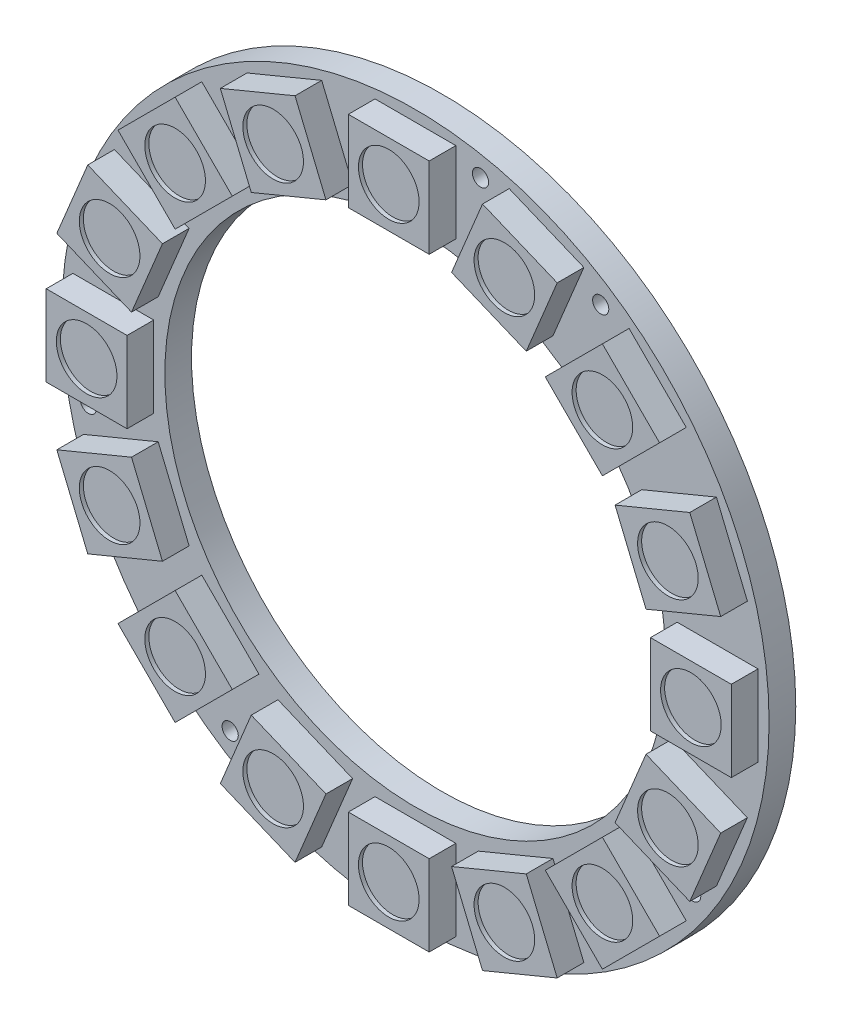
SolidWorks part; units mm, degrees
ref_plane "Front Plane" through (0, 0, 0) normal (0, 0, 1) x (1, 0, 0)
ref_plane "Top Plane" through (0, 0, 0) normal (0, 1, 0) x (1, 0, 0)
ref_plane "Right Plane" through (0, 0, 0) normal (1, 0, 0) x (0, 0, -1)
sketch "Sketch1" plane through (0, 0, 0) normal (0, 0, 1) x (1, 0, 0)
  circle A0 centre (0, 0) radius 15.748
  circle A1 centre (0, 0) radius 22.225
  dimension "D1" = 31.496
  dimension "D2" = 44.45
extrude "Boss-Extrude1" add sketch "Sketch1" along normal blind 1.6764
sketch "Sketch2" plane through (0, 0, 1.6764) normal (0, 0, 1) x (1, 0, 0)
  line L0 (0, 0) -> (0, 15.748) construction
  line L1 (0, 15.748) -> (0, 18.9865) construction
  line L2 (-2.54, 21.5265) -> (2.54, 21.5265)
  line L3 (-2.54, 21.5265) -> (-2.54, 16.4465)
  line L4 (-2.54, 16.4465) -> (2.54, 16.4465)
  line L5 (2.54, 21.5265) -> (2.54, 16.4465)
  line L6 (-2.54, 21.5265) -> (2.54, 16.4465) construction
  line L7 (-2.54, 16.4465) -> (2.54, 21.5265) construction
  line L8 (0, 18.9865) -> (0, 22.225) construction
  circle A0 centre (0, 0) radius 15.748 construction
  circle A1 centre (0, 0) radius 22.225 construction
  point P6 (0, 18.9865)
  dimension "D1" = 5.08
  dimension "D2" = 5.08
extrude "Boss-Extrude2" add sketch "Sketch2" along normal blind 1.6764
sketch "Sketch3" plane through (0, 0, 3.3528) normal (0, 0, 1) x (1, 0, 0)
  line L0 (0, 16.4465) -> (0, 21.5265) construction
  line L1 (-2.54, 16.4465) -> (2.54, 16.4465) construction
  line L2 (2.54, 21.5265) -> (-2.54, 21.5265) construction
  circle A0 centre (0, 18.9865) radius 1.905
  point P8 (0.4998, 19.7134)
  dimension "D1" = 3.81
extrude "Cut-Extrude1" cut sketch "Sketch3" against normal blind 0.254
pattern_circular "CirPattern1" count 16 over 360 about axis through (0, 0, 0) along (0, 0, 1) of "Cut-Extrude1", "Boss-Extrude2"
sketch "Sketch4" plane through (0, 0, 1.6764) normal (0, 0, 1) x (1, 0, 0)
  line L0 (4.0881, 20.5524) -> (4.3359, 21.798) construction
  line L1 (4.0881, 20.5524) -> (0, 0) construction
  line L2 (4.1872, 21.0506) -> (4.5674, 20.975) construction
  line L3 (2.54, 16.4465) -> (3.2436, 16.3066) construction
  line L4 (3.2436, 16.3066) -> (3.9471, 16.1666) construction
  circle A0 centre (4.0881, 20.5524) radius 0.508
  circle A1 centre (0, 0) radius 22.225 construction
  dimension "D1" = 1.016
  dimension "D2" = 0.762
extrude "Cut-Extrude2" cut sketch "Sketch4" against normal through all
pattern_circular "CirPattern2" count 16 over 360 about axis through (0, 0, 0) along (0, 0, 1) skipping 1, 2, 3, 4, 6, 8, 9, 12, 13, 14 of "Cut-Extrude2"
